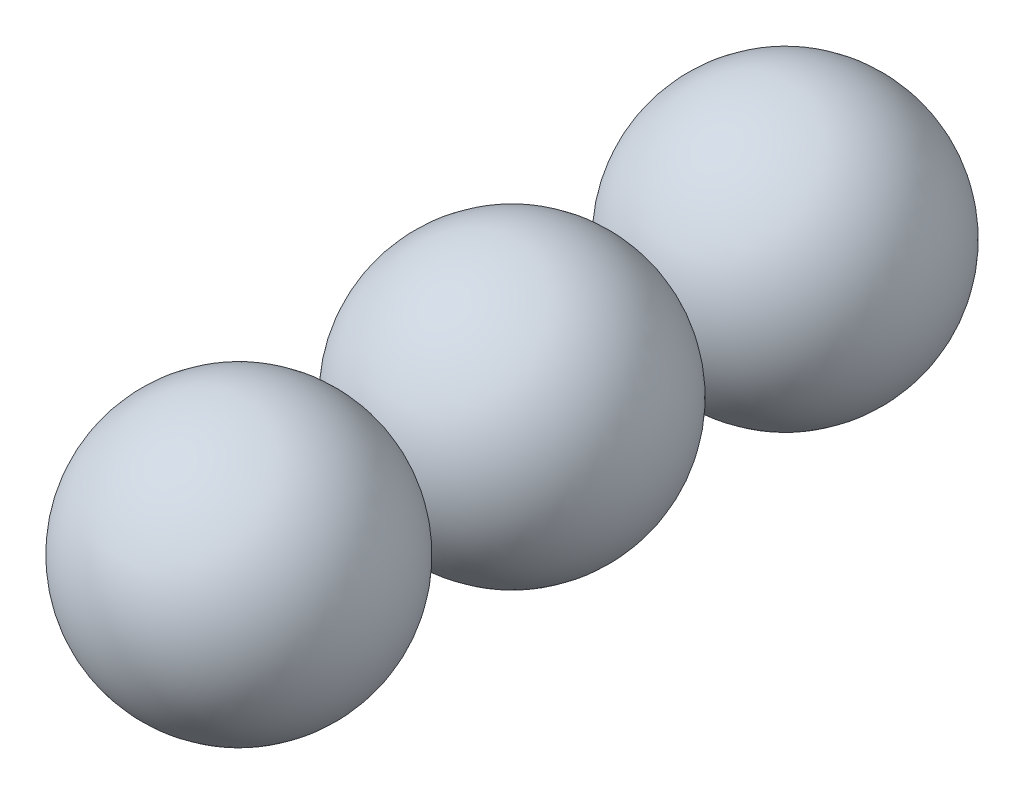
SolidWorks part; units mm, degrees
ref_plane "前基準面" through (0, 0, 0) normal (0, 0, 1) x (1, 0, 0)
ref_plane "上基準面" through (0, 0, 0) normal (0, 1, 0) x (1, 0, 0)
ref_plane "右基準面" through (0, 0, 0) normal (1, 0, 0) x (0, 0, -1)
sketch "草圖1" plane through (0, 0, 0) normal (0, 0, 1) x (1, 0, 0)
  line L0 (0, 30) -> (0, -30)
  arc A0 (0, -30) -> (0, 30) centre (0, 0) ccw
  dimension "D1" = 60
revolve "旋轉1" add sketch "草圖1" angle 360 about L0
pattern_linear "直線複製排列1" count 3 spacing 60 along (0, 0, 1) of "旋轉1"
